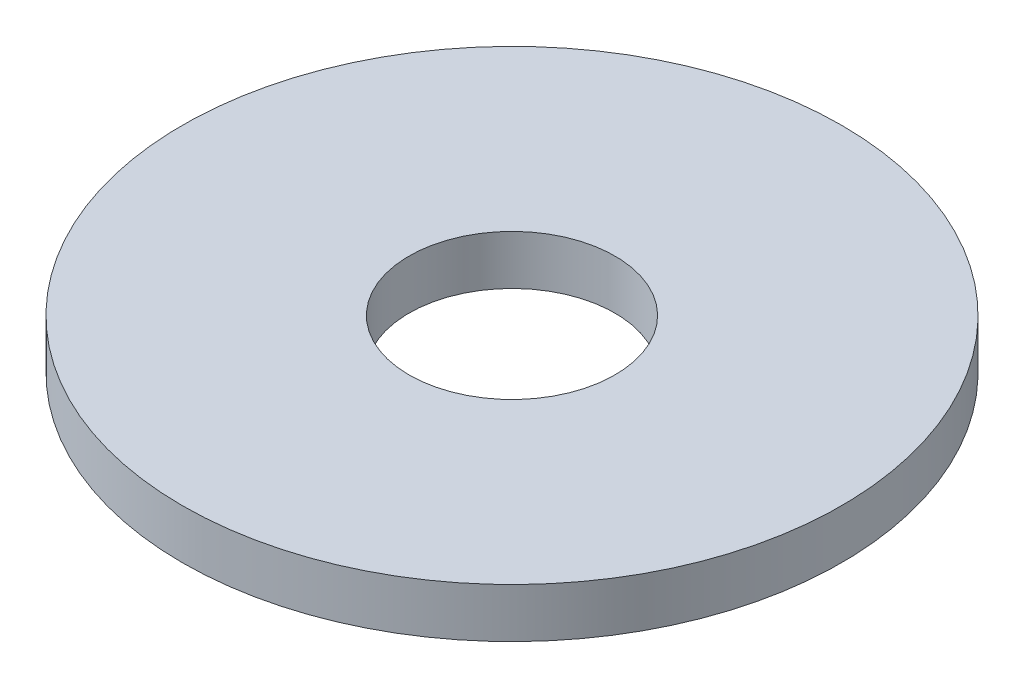
SolidWorks part; units mm, degrees
material "Plain Carbon Steel"
ref_plane "Front Plane" through (0, 0, 0) normal (0, 0, 1) x (1, 0, 0)
ref_plane "Top Plane" through (0, 0, 0) normal (0, 1, 0) x (1, 0, 0)
ref_plane "Right Plane" through (0, 0, 0) normal (1, 0, 0) x (0, 0, -1)
sketch "Sketch1" plane through (0, 0, 0) normal (0, 1, 0) x (1, 0, 0)
  circle A0 centre (0, 0) radius 20
  circle A1 centre (0, 0) radius 6.25
  dimension "D1" = 40
  dimension "D2" = 12.5
extrude "Boss-Extrude1" add sketch "Sketch1" along normal mid plane 3
